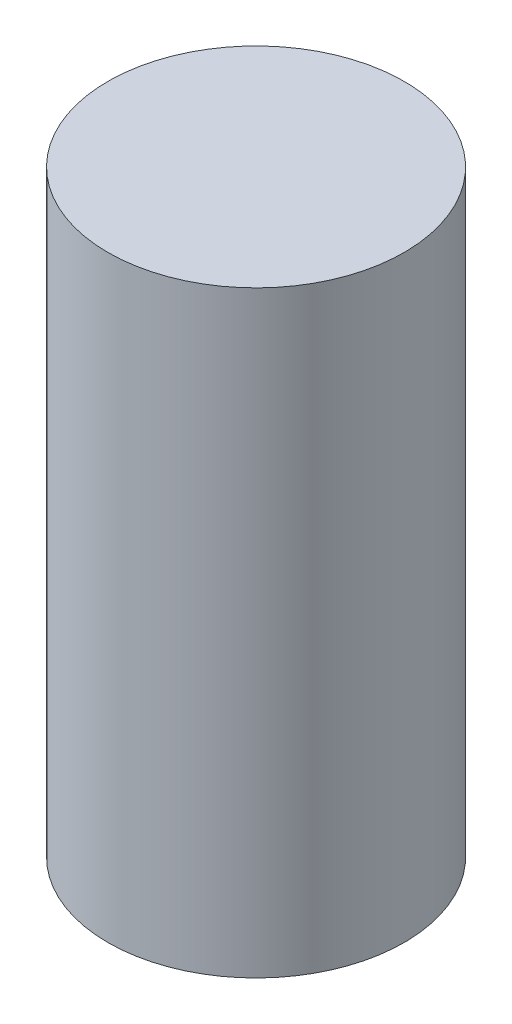
SolidWorks part; units mm, degrees
ref_plane "Front Plane" through (0, 0, 0) normal (0, 0, 1) x (1, 0, 0)
ref_plane "Top Plane" through (0, 0, 0) normal (0, 1, 0) x (1, 0, 0)
ref_plane "Right Plane" through (0, 0, 0) normal (1, 0, 0) x (0, 0, -1)
sketch "Sketch1" plane through (0, 0, 0) normal (0, 1, 0) x (1, 0, 0)
  circle A1 centre (0, 0) radius 29.75
  dimension "D1" = 59.5
extrude "Boss-Extrude1" add sketch "Sketch1" along normal blind 120
